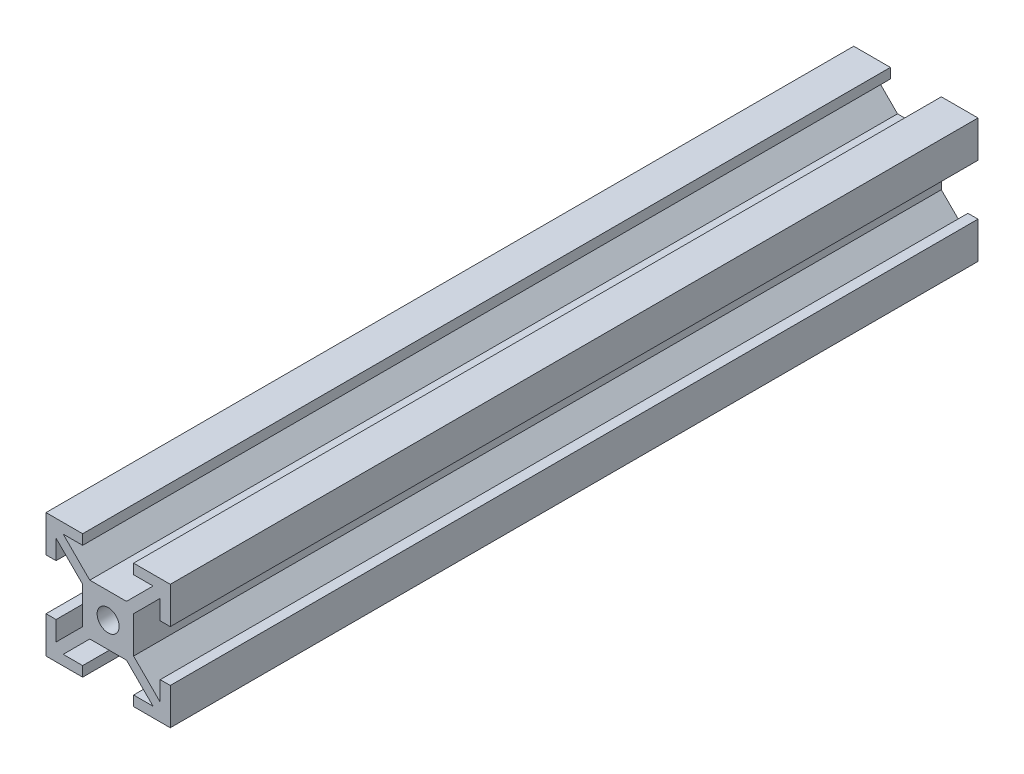
SolidWorks part; units mm, degrees
ref_plane "Front Plane" through (0, 0, 0) normal (0, 0, 1) x (1, 0, 0)
ref_plane "Top Plane" through (0, 0, 0) normal (0, 1, 0) x (1, 0, 0)
ref_plane "Right Plane" through (0, 0, 0) normal (1, 0, 0) x (0, 0, -1)
sketch "Sketch1" plane through (0, 0, 0) normal (0, 0, 1) x (1, 0, 0)
  line L0 (-8.38, 4.1) -> (-10, 4.1)
  line L1 (-2.9545, 4.1) -> (2.9545, 4.1)
  line L2 (-4.1, 2.9545) -> (-4.1, -2.9545)
  line L3 (-2.9545, -4.1) -> (2.9545, -4.1)
  line L4 (4.1, 2.9545) -> (4.1, -2.9545)
  line L5 (-4.1, 4.1) -> (4.1, -4.1) construction
  line L6 (-4.1, -4.1) -> (4.1, 4.1) construction
  line L7 (-10, 10) -> (-4.1, 10)
  line L8 (-10, 10) -> (-10, 4.1)
  line L9 (-10, -10) -> (-4.1, -10)
  line L10 (10, 10) -> (10, 4.1)
  line L11 (-10, 10) -> (10, -10) construction
  line L12 (-10, -10) -> (10, 10) construction
  line L13 (-7.2345, 8.38) -> (-4.1, 8.38)
  line L14 (-8.38, 7.2345) -> (-8.38, 4.1)
  line L15 (-7.2345, -8.38) -> (-4.1, -8.38)
  line L16 (8.38, 7.2345) -> (8.38, 4.1)
  line L17 (-8.38, 8.38) -> (8.38, -8.38) construction
  line L18 (-8.38, -8.38) -> (8.38, 8.38) construction
  line L19 (-4.1, 8.38) -> (-4.1, 10)
  line L20 (4.1, 10) -> (4.1, 8.38)
  line L21 (8.38, 4.1) -> (10, 4.1)
  line L22 (-8.38, -4.1) -> (-10, -4.1)
  line L23 (-4.1, -8.38) -> (-4.1, -10)
  line L24 (8.38, -4.1) -> (10, -4.1)
  line L25 (4.1, -8.38) -> (4.1, -10)
  line L26 (-5.464, 5.464) -> (-4.8912, 6.0368) construction
  line L27 (-4.1, 2.9545) -> (-8.38, 7.2345)
  line L28 (-2.9545, 4.1) -> (-7.2345, 8.38)
  line L29 (0, 11.3108) -> (0, -17.1823) construction
  line L30 (-16.7028, 0) -> (14.4032, 0) construction
  line L31 (-2.9545, -4.1) -> (-7.2345, -8.38)
  line L32 (-4.1, -2.9545) -> (-8.38, -7.2345)
  line L33 (2.9545, -4.1) -> (7.2345, -8.38)
  line L34 (4.1, -2.9545) -> (8.38, -7.2345)
  line L35 (4.1, 2.9545) -> (8.38, 7.2345)
  line L36 (2.9545, 4.1) -> (7.2345, 8.38)
  line L37 (4.1, 8.38) -> (7.2345, 8.38)
  line L38 (4.1, 10) -> (10, 10)
  line L39 (-8.38, -4.1) -> (-8.38, -7.2345)
  line L40 (-10, -4.1) -> (-10, -10)
  line L41 (8.38, -4.1) -> (8.38, -7.2345)
  line L42 (10, -4.1) -> (10, -10)
  line L43 (4.1, -8.38) -> (7.2345, -8.38)
  line L44 (4.1, -10) -> (10, -10)
  circle A0 centre (0, 0) radius 1.77
  point P0 (0, 0)
  point P6 (0, 0)
  dimension "D5" = 3.54
  dimension "D1" = 8.2
  dimension "D2" = 20
  dimension "D3" = 8.2
  dimension "D4" = 20
  dimension "D6" = 16.76
  dimension "D7" = 16.76
  dimension "D8" = 0.81
  dimension "D9" = 135
  dimension "D10" = 7.7696
  dimension "D11" = 5.0536
extrude "Boss-Extrude1" add sketch "Sketch1" along normal blind 130
